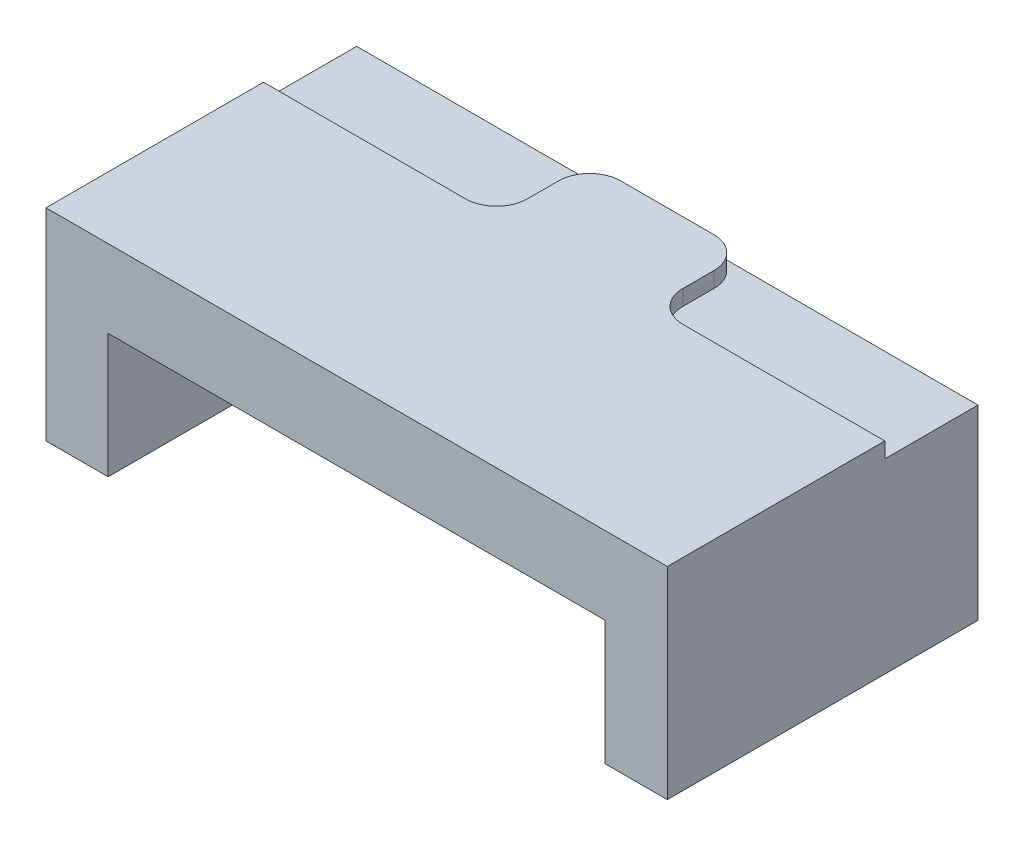
SolidWorks part; units mm, degrees
ref_plane "Front Plane" through (0, 0, 0) normal (0, 0, 1) x (1, 0, 0)
ref_plane "Top Plane" through (0, 0, 0) normal (0, 1, 0) x (1, 0, 0)
ref_plane "Right Plane" through (0, 0, 0) normal (1, 0, 0) x (0, 0, -1)
sketch "Sketch1" plane through (0, 0, 0) normal (0, 0, 1) x (1, 0, 0)
  line L0 (0, 0) -> (0, 60) construction
  line L1 (0, 60) -> (-100, 60)
  line L2 (-100, 60) -> (-100, 0)
  line L3 (-100, 0) -> (-80, 0)
  line L4 (-80, 0) -> (-80, 40)
  line L5 (-80, 40) -> (0, 40)
  line L6 (0, 40) -> (0, 60)
  dimension "D1" = 60
  dimension "D2" = 20
  dimension "D3" = 20
  dimension "D4" = 100
extrude "Boss-Extrude1" add sketch "Sketch1" along normal blind 100
mirror "Mirror1" about plane through (0, 40, 100) normal (-1, 0, 0) of "Boss-Extrude1"
sketch "Sketch2" plane through (0, 60, 0) normal (0, 1, 0) x (1, 0, 0)
  line L0 (100, -100) -> (100, 0) construction
  line L1 (-100, -100) -> (100, -100)
  line L2 (-100, -100) -> (-100, -30)
  line L3 (-100, -30) -> (100, -30)
  line L4 (100, -100) -> (100, -30)
  line L5 (100, 0) -> (-100, 0) construction
  line L6 (-25, 0) -> (25, 0)
  line L7 (-25, 0) -> (-25, -30)
  line L8 (-25, -30) -> (25, -30)
  line L9 (25, 0) -> (25, -30)
  point P13 (0, 0)
  line M9 (100, 0) -> (-100, 0)
  line M10 (-100, 0) -> (-100, -100)
  line M11 (-100, -100) -> (100, -100)
  line M12 (100, -100) -> (100, 0)
  dimension "D1" = 70
  dimension "D2" = 50
extrude "Boss-Extrude2" add sketch "Sketch2" along normal blind 5 contours L3 M10 M11 M12 | L9 L7 L3 M9
fillet "Fillet1" radius 10 4 edges at (-25, 62.5, 30) (-25, 62.5, 0) (25, 62.5, 0) (25, 62.5, 30)
scale "Scale1" scale about centroid uniform scaling yes scale factor 10
